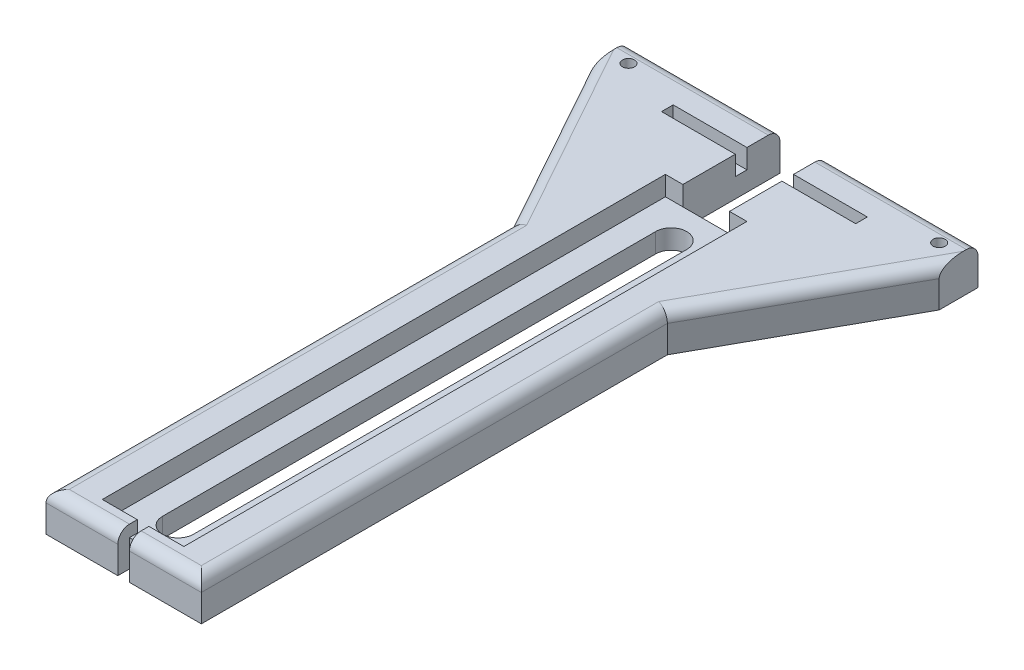
SolidWorks part; units mm, degrees
ref_plane "Front Plane" through (0, 0, 0) normal (0, 0, 1) x (1, 0, 0)
ref_plane "Top Plane" through (0, 0, 0) normal (0, 1, 0) x (1, 0, 0)
ref_plane "Right Plane" through (0, 0, 0) normal (1, 0, 0) x (0, 0, -1)
sketch "Sketch1" plane through (0, 0, 0) normal (0, 1, 0) x (1, 0, 0)
  line L0 (0, 0) -> (-45, 0)
  line L1 (-45, 0) -> (-45, -10)
  line L3 (-20, -55) -> (-20, -175)
  line L4 (-20, -175) -> (0, -175)
  line L5 (0, -175) -> (0, -165)
  line L6 (0, -34) -> (0, -161) construction
  line L7 (4, -34) -> (4, -161)
  line L8 (-4, -34) -> (-4, -161)
  line L9 (0, -30) -> (0, 0)
  line L10 (-45, -10) -> (-20, -55)
  arc A0 (4, -34) -> (-4, -34) centre (0, -34) ccw
  arc A1 (-4, -161) -> (4, -161) centre (0, -161) ccw
  circle A2 centre (-40, -5) radius 1.55
  point P9 (0, -97.5)
  dimension "D5" = 4
  dimension "D8" = 3.1
  dimension "D1" = 45
  dimension "D2" = 175
  dimension "D3" = 30
  dimension "D4" = 10
  dimension "D6" = 20
  dimension "D7" = 10
  dimension "D9" = 5
  dimension "D10" = 40
  dimension "D11" = 120
extrude "Boss-Extrude1" add sketch "Sketch1" along normal blind 10
sketch "Sketch2" plane through (0, 10, 0) normal (0, 1, 0) x (1, 0, 0)
  line L0 (0, -175) -> (0, -165) construction
  line L5 (0, 0) -> (-45, 0) construction
  line L6 (0, -25) -> (-10.5, -25)
  line L7 (0, -25) -> (0, -170)
  line L8 (0, -170) -> (-10.5, -170)
  line L9 (-10.5, -25) -> (-10.5, -170)
  line L10 (-20, -175) -> (0, -175) construction
  point P8 (0, 0)
  dimension "D1" = 25
  dimension "D2" = 10.5
  dimension "D3" = 5
extrude "Cut-Extrude1" cut sketch "Sketch2" against normal blind 5
mirror "Mirror1" about plane through (0, 0, 0) normal (1, 0, 0) of "Cut-Extrude1", "Boss-Extrude1"
sketch "Sketch3" plane through (0, 10, 0) normal (0, 1, 0) x (1, 0, 0)
  line L0 (45, 0) -> (-45, 0) construction
  line L1 (-6, 0) -> (6, 0)
  line L2 (-6, 0) -> (-6, -25)
  line L3 (-6, -25) -> (6, -25)
  line L4 (6, 0) -> (6, -25)
  line L5 (10.5, -25) -> (-10.5, -25) construction
  dimension "D1" = 6
  dimension "D2" = 12
extrude "Cut-Extrude2" cut sketch "Sketch3" against normal through all
sketch "Sketch4" plane through (0, 10, 0) normal (0, 1, 0) x (1, 0, 0)
  line L0 (45, 0) -> (6, 0) construction
  line L1 (-25, -8.5) -> (25, -8.5)
  line L2 (-25, -8.5) -> (-25, -11.5)
  line L3 (-25, -11.5) -> (25, -11.5)
  line L4 (25, -8.5) -> (25, -11.5)
  dimension "D1" = 3
  dimension "D2" = 50
  dimension "D3" = 25
  dimension "D4" = 8.5
extrude "Cut-Extrude3" cut sketch "Sketch4" against normal blind 5
fillet "Fillet1" radius 3 7 edges at (-25.5, 10, 0) (25.5, 10, 0) (32.5, 10, 32.5) (20, 10, 115) (-32.5, 10, 32.5) (-20, 10, 115) (0, 10, 175)
sketch "Sketch6" plane through (0, 0, 0) normal (0, -1, 0) x (1, 0, 0)
  line L1 (-36.9094, 3.9946) -> (-37.584, 7.1738)
  line L2 (-37.584, 7.1738) -> (-40.6745, 8.1792)
  line L3 (-40.6745, 8.1792) -> (-43.0906, 6.0054)
  line L4 (-43.0906, 6.0054) -> (-42.416, 2.8262)
  line L5 (-42.416, 2.8262) -> (-39.3255, 1.8208)
  line L6 (-39.3255, 1.8208) -> (-36.9094, 3.9946)
  line L7 (42.1391, 2.5532) -> (43.1885, 5.6291)
  line L8 (43.1885, 5.6291) -> (41.0495, 8.0759)
  line L9 (41.0495, 8.0759) -> (37.8609, 7.4468)
  line L10 (37.8609, 7.4468) -> (36.8115, 4.3709)
  line L11 (36.8115, 4.3709) -> (38.9505, 1.9241)
  line L12 (38.9505, 1.9241) -> (42.1391, 2.5532)
  circle A0 centre (40, 5) radius 3.25
  circle A1 centre (-40, 5) radius 3.25
  circle A2 centre (-40, 5) radius 2.8146 construction
  circle A3 centre (40, 5) radius 2.8146 construction
  circle M24 centre (-40, 5) radius 1.55
  circle M25 centre (40, 5) radius 1.55
  dimension "D1" = 6.5
  dimension "D2" = 6.5
extrude "Cut-Extrude4" cut sketch "Sketch6" against normal blind 5 contours L5 L6 L1 L2 L3 L4 M24 | L11 L12 L7 L8 L9 L10 M25
chamfer "Chamfer2" distance 1 angle 45 12 edges at (37.881, 5, 3.1475) (40.5448, 5, 2.2386) (42.6638, 5, 4.0911) (42.119, 5, 6.8525) (39.4552, 5, 7.7614) (37.3362, 5, 5.9089) (-42.7533, 5, 4.4158) (-40.8707, 5, 2.3235) (-38.1175, 5, 2.9077) (-37.2467, 5, 5.5842) (-39.1293, 5, 7.6765) (-41.8825, 5, 7.0923)
sketch "Sketch7" plane through (0, 0, 175) normal (0, 0, 1) x (1, 0, 0)
  line L0 (20, 7) -> (-20, 7) construction
  line L1 (-1.5, 7) -> (1.5, 7)
  line L2 (-1.5, 7) -> (-1.5, 10)
  line L3 (-1.5, 10) -> (1.5, 10)
  line L4 (1.5, 7) -> (1.5, 10)
  line L5 (-17, 10) -> (17, 10) construction
  line L6 (-20, 0) -> (20, 0) construction
  line L7 (-1.5, 0) -> (1.5, 0)
  line L8 (-1.5, 0) -> (-1.5, 3)
  line L9 (-1.5, 3) -> (1.5, 3)
  line L10 (1.5, 0) -> (1.5, 3)
  dimension "D1" = 1.5
  dimension "D2" = 1.5
extrude "Cut-Extrude5" cut sketch "Sketch7" against normal blind 12
sketch "Sketch8" plane through (0, 7, 0) normal (0, 1, 0) x (1, 0, 0)
  line L1 (-1.5, -175) -> (1.5, -175)
  line L2 (-1.5, -175) -> (-1.5, -172)
  line L3 (-1.5, -172) -> (1.5, -172)
  line L4 (1.5, -175) -> (1.5, -172)
extrude "Cut-Extrude6" cut sketch "Sketch8" against normal through all
